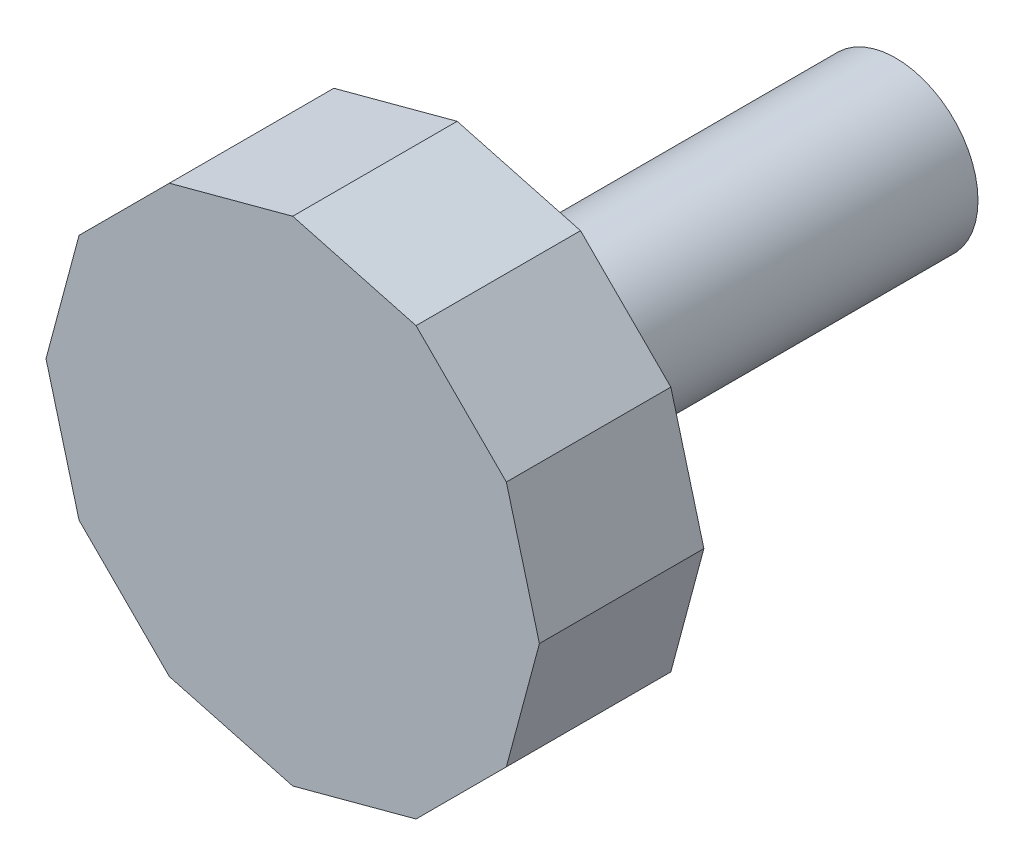
SolidWorks part; units mm, degrees
ref_plane "前视基准面" through (0, 0, 0) normal (0, 0, 1) x (1, 0, 0)
ref_plane "上视基准面" through (0, 0, 0) normal (0, 1, 0) x (1, 0, 0)
ref_plane "右视基准面" through (0, 0, 0) normal (1, 0, 0) x (0, 0, -1)
other "Configuration Table"
sketch "草图1" plane through (0, 0, 0) normal (0, 0, 1) x (1, 0, 0)
  circle A0 centre (0, 0) radius 1.5
extrude "M3x8简化螺杆" add sketch "草图1" along normal blind 8
sketch "草图2" plane through (0, 0, 0) normal (0, 0, 1) x (1, 0, 0)
  line L0 (4.5, 0) -> (3.8971, 2.25)
  line L1 (3.8971, 2.25) -> (2.25, 3.8971)
  line L2 (2.25, 3.8971) -> (0, 4.5)
  line L3 (0, 4.5) -> (-2.25, 3.8971)
  line L4 (-2.25, 3.8971) -> (-3.8971, 2.25)
  line L5 (-3.8971, 2.25) -> (-4.5, 0)
  line L6 (-4.5, 0) -> (-3.8971, -2.25)
  line L7 (-3.8971, -2.25) -> (-2.25, -3.8971)
  line L8 (-2.25, -3.8971) -> (0, -4.5)
  line L9 (0, -4.5) -> (2.25, -3.8971)
  line L10 (2.25, -3.8971) -> (3.8971, -2.25)
  line L11 (3.8971, -2.25) -> (4.5, 0)
extrude "D9十二边手拧头" add sketch "草图2" along normal blind 3 from offset 8
